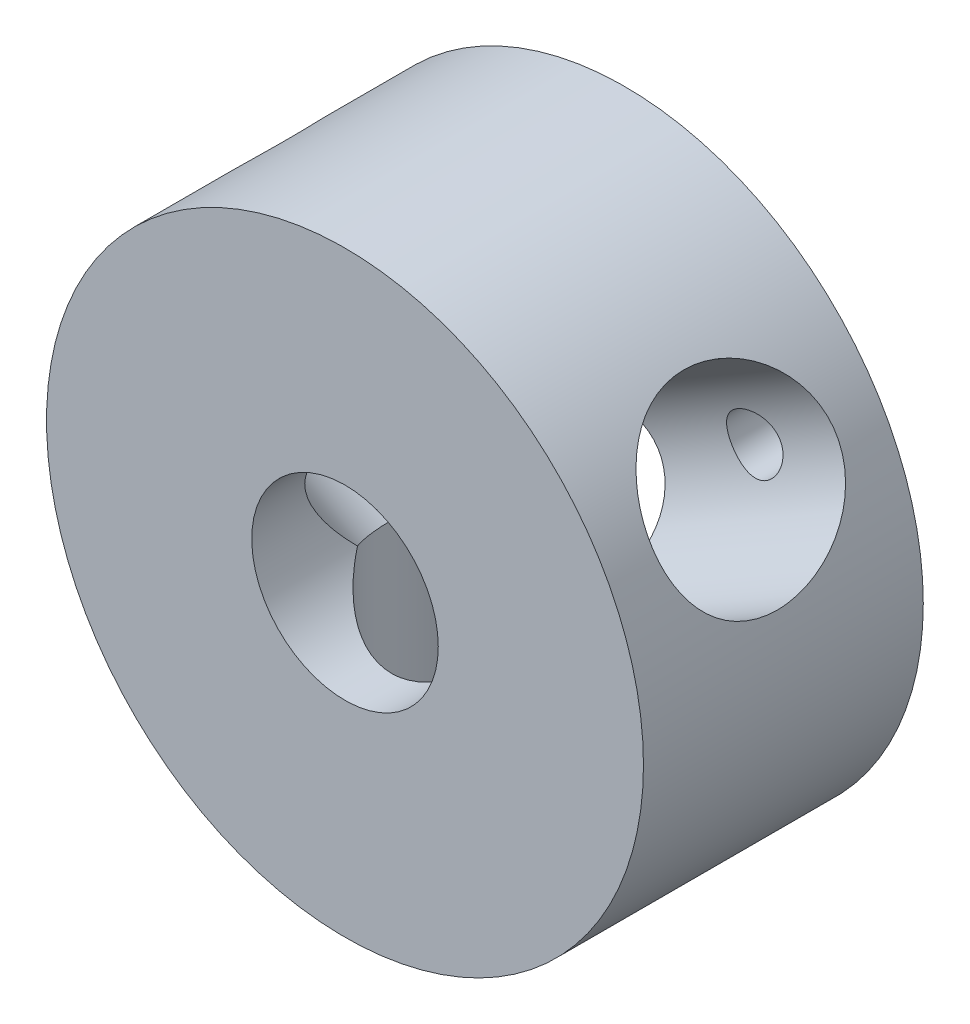
SolidWorks part; units mm, degrees
material "Plain Carbon Steel"
ref_plane "Front Plane" through (0, 0, 0) normal (0, 0, 1) x (1, 0, 0)
ref_plane "Top Plane" through (0, 0, 0) normal (0, 1, 0) x (1, 0, 0)
ref_plane "Right Plane" through (0, 0, 0) normal (1, 0, 0) x (0, 0, -1)
sketch "Sketch1" plane through (0, 0, 0) normal (0, 0, 1) x (1, 0, 0)
  circle A0 centre (0, 0) radius 32
  circle A1 centre (0, 0) radius 10
  dimension "D1" = 64
  dimension "D2" = 20
extrude "Boss-Extrude1" add sketch "Sketch1" along normal mid plane 30
sketch "Sketch2" plane through (0, 0, 0) normal (0, 1, 0) x (1, 0, 0)
  circle A0 centre (0, 0) radius 10
  dimension "D1" = 20
extrude "Cut-Extrude1" cut sketch "Sketch2" against normal through all
pattern_circular "CirPattern1" count 3 over 360 about axis through (0, 0, 15) along (0, 0, -1) of "Cut-Extrude1"
sketch "Sketch4" plane through (0, 0, -15) normal (0, 0, 1) x (1, 0, 0)
  line L0 (0, 0) -> (0, -32) construction
  line L2 (0, 0) -> (-35.061, 0) construction
  line L3 (0, -32) -> (0, -22)
  circle A0 centre (0, 0) radius 32 construction
  circle A1 centre (0, -22) radius 3
  dimension "D1" = 270
extrude "Cut-Extrude3" cut sketch "Sketch4" along normal blind 11 contours A1
pattern_circular "CirPattern2" count 3 over 360 about axis through (0, 0, 0) along (0, 0, 1) of "Cut-Extrude3"
